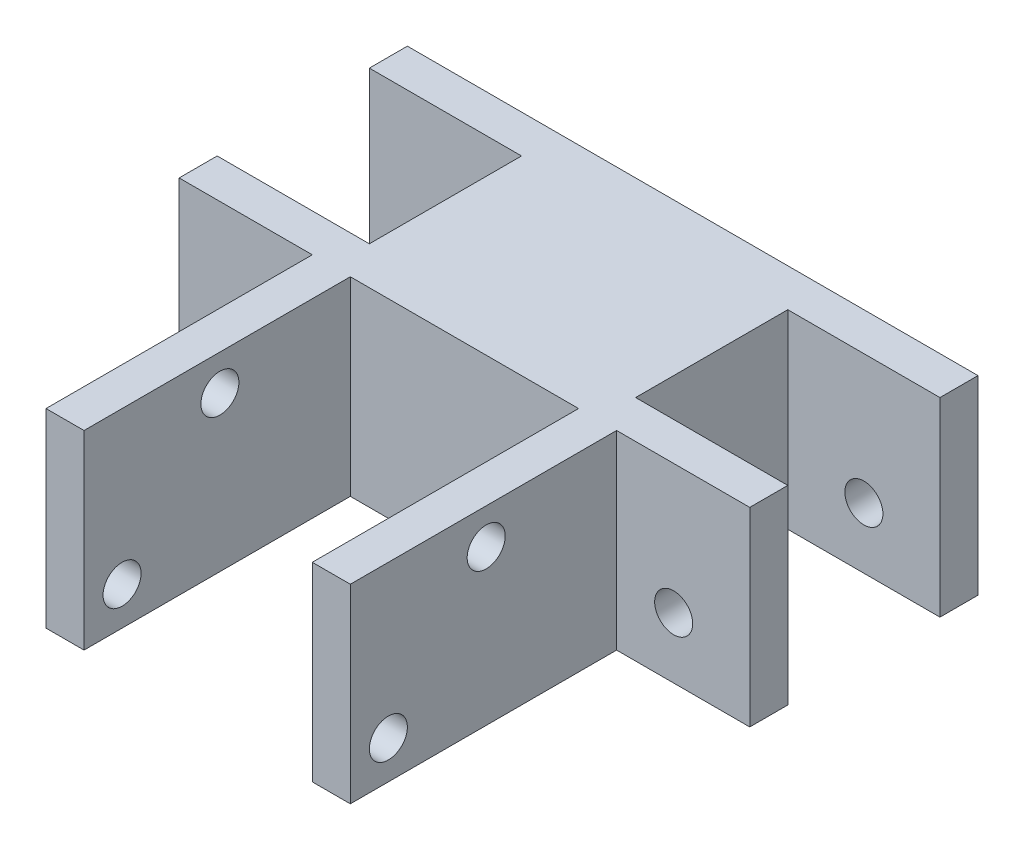
SolidWorks part; units mm, degrees
material "6061-T6 (SS)"
ref_plane "Front Plane" through (0, 0, 0) normal (0, 0, 1) x (1, 0, 0)
ref_plane "Top Plane" through (0, 0, 0) normal (0, 1, 0) x (1, 0, 0)
ref_plane "Right Plane" through (0, 0, 0) normal (1, 0, 0) x (0, 0, -1)
sketch "Sketch1" plane through (0, 0, 0) normal (0, 1, 0) x (1, 0, 0)
  line L0 (-22.225, 19.05) -> (22.225, 19.05)
  line L1 (-22.225, 12.7) -> (-22.225, -12.7)
  line L2 (-47.625, -19.05) -> (-25.4, -19.05)
  line L3 (22.225, 12.7) -> (22.225, -12.7)
  line L4 (-25.4, -19.05) -> (-25.4, -63.5)
  line L5 (-25.4, -63.5) -> (-19.05, -63.5)
  line L6 (-19.05, -63.5) -> (-19.05, -19.05)
  line L7 (-22.225, 19.05) -> (-47.625, 19.05)
  line L8 (-19.05, -19.05) -> (19.05, -19.05)
  line L9 (-22.225, 12.7) -> (-47.625, 12.7)
  line L10 (-47.625, 19.05) -> (-47.625, 12.7)
  line L11 (-22.225, 12.7) -> (22.225, -12.7) construction
  line L13 (-22.225, -12.7) -> (-47.625, -12.7)
  line L14 (-47.625, -19.05) -> (-47.625, -12.7)
  line L15 (22.225, 19.05) -> (47.625, 19.05)
  line L17 (22.225, 12.7) -> (47.625, 12.7)
  line L18 (47.625, 19.05) -> (47.625, 12.7)
  line L19 (25.4, -19.05) -> (47.625, -19.05)
  line L21 (22.225, -12.7) -> (47.625, -12.7)
  line L22 (47.625, -19.05) -> (47.625, -12.7)
  line L28 (25.4, -19.05) -> (25.4, -63.5)
  line L29 (25.4, -63.5) -> (19.05, -63.5)
  line L30 (19.05, -19.05) -> (19.05, -63.5)
  point P7 (0, 0)
  dimension "D1" = 6.35
  dimension "D2" = 44.45
  dimension "D3" = 25.4
  dimension "D4" = 44.45
  dimension "D5" = 25.4
  dimension "D6" = 22.225
extrude "Boss-Extrude1" add sketch "Sketch1" along normal blind 31.75
sketch "Sketch2" plane through (0, 0, 19.05) normal (0, 0, 1) x (1, 0, 0)
  line L0 (25.4, 0) -> (47.625, 0) construction
  line L2 (-47.625, 0) -> (-25.4, 0) construction
  line L7 (-47.625, 31.75) -> (-47.625, 0) construction
  line L8 (47.625, 31.75) -> (47.625, 0) construction
  circle A0 centre (34.925, 10.16) radius 3.175
  circle A1 centre (-34.925, 10.16) radius 3.175
  dimension "D1" = 10.16
  dimension "D2" = 12.7
  dimension "D3" = 10.16
  dimension "D4" = 6.35
  dimension "D5" = 6.35
  dimension "D6" = 12.7
extrude "Cut-Extrude1" cut sketch "Sketch2" against normal blind 6.35
mirror "Mirror1" about plane through (0, 0, 0) normal (0, 0, 1) of "Cut-Extrude1"
sketch "Sketch4" plane through (-25.4, 0, 0) normal (-1, 0, 0) x (0, 0, 1)
  line L0 (57.15, 6.35) -> (40.8232, 25.8075) construction
  line L1 (19.05, 0) -> (63.5, 0) construction
  line L4 (63.5, 31.75) -> (63.5, 0) construction
  circle A0 centre (40.8232, 25.8075) radius 3.175
  circle A1 centre (57.15, 6.35) radius 3.175
  dimension "D2" = 25.4
  dimension "D3" = 6.35
  dimension "D4" = 6.35
  dimension "D5" = 6.35
  dimension "D1" = 50
extrude "Cut-Extrude2" cut sketch "Sketch4" against normal blind 6.35
mirror "Mirror2" about plane through (0, 0, 0) normal (1, 0, 0) of "Cut-Extrude2"
